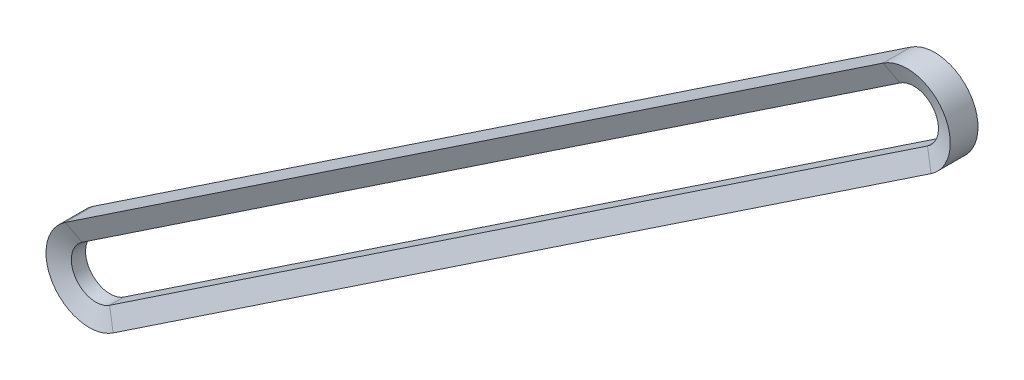
SolidWorks part; units mm, degrees
ref_plane "前视基准面" through (0, 0, 0) normal (0, 0, 1) x (1, 0, 0)
ref_plane "上视基准面" through (0, 0, 0) normal (0, 1, 0) x (1, 0, 0)
ref_plane "右视基准面" through (0, 0, 0) normal (1, 0, 0) x (0, 0, -1)
sketch "草图2" plane through (0, 0, 0) normal (0, 0, 1) x (1, 0, 0)
  line L0 (0, 0) -> (1, 0) construction
  line L1 (0, 0) -> (0, 1) construction
  line L2 (9.5778, 0.0288) -> (-166.6496, -117.8126)
  line L3 (-172.5417, -109.0012) -> (3.6856, 8.8403)
  arc A0 (3.6856, 8.8403) -> (9.5778, 0.0288) centre (6.6317, 4.4345) cw
  arc A1 (-166.6496, -117.8126) -> (-172.5417, -109.0012) centre (-169.5956, -113.4069) cw
ref_plane "基准面4" through (9.5778, 0.0288, 0) normal (-0.8313, -0.5559, 0) x (0, 0, -1)
sketch "草图3" plane through (9.5778, 0.0288, 0) normal (-0.8313, -0.5559, 0) x (0, 0, -1)
  line L0 (-1.535, -10.6) -> (1.535, -10.6)
  line L1 (0, 0) -> (0, -10.6) construction
  line L2 (0, 0) -> (0, -10.6) construction
  line L3 (1.535, -10.6) -> (2.9909, -14.6)
  line L4 (2.9909, -14.6) -> (-2.9909, -14.6)
  line L5 (0, -14.6) -> (0, -10.6)
  line L6 (-1.535, -10.6) -> (-2.9909, -14.6)
  dimension "D1" = 110
  dimension "D2" = 4
sweep "扫描2" add profiles "草图3" path "草图2"
